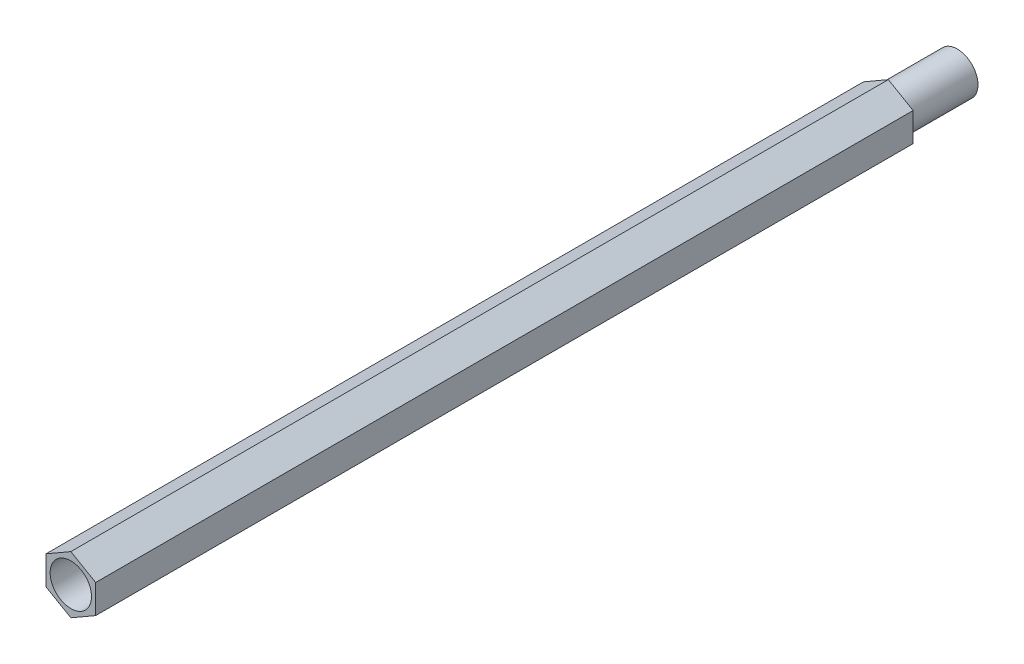
SolidWorks part; units mm, degrees
ref_plane "前视基准面" through (0, 0, 0) normal (0, 0, 1) x (1, 0, 0)
ref_plane "上视基准面" through (0, 0, 0) normal (0, 1, 0) x (1, 0, 0)
ref_plane "右视基准面" through (0, 0, 0) normal (1, 0, 0) x (0, 0, -1)
sketch "草图1" plane through (0, 0, 0) normal (0, 0, 1) x (1, 0, 0)
  line L1 (0, 2.0785) -> (-1.8, 1.0392)
  line L2 (-1.8, 1.0392) -> (-1.8, -1.0392)
  line L3 (-1.8, -1.0392) -> (0, -2.0785)
  line L4 (0, -2.0785) -> (1.8, -1.0392)
  line L5 (1.8, -1.0392) -> (1.8, 1.0392)
  line L6 (1.8, 1.0392) -> (0, 2.0785)
  circle A0 centre (0, 0) radius 1.8 construction
  circle A1 centre (0, 0) radius 1.5
extrude "凸台-拉伸1" add sketch "草图1" along normal blind 59.25
sketch "草图2" plane through (0, 0, 0) normal (0, 0, -1) x (-1, 0, 0)
  circle A0 centre (0, 0) radius 1.5
extrude "凸台-拉伸2" add sketch "草图2" along normal mid plane 10 contours A0
